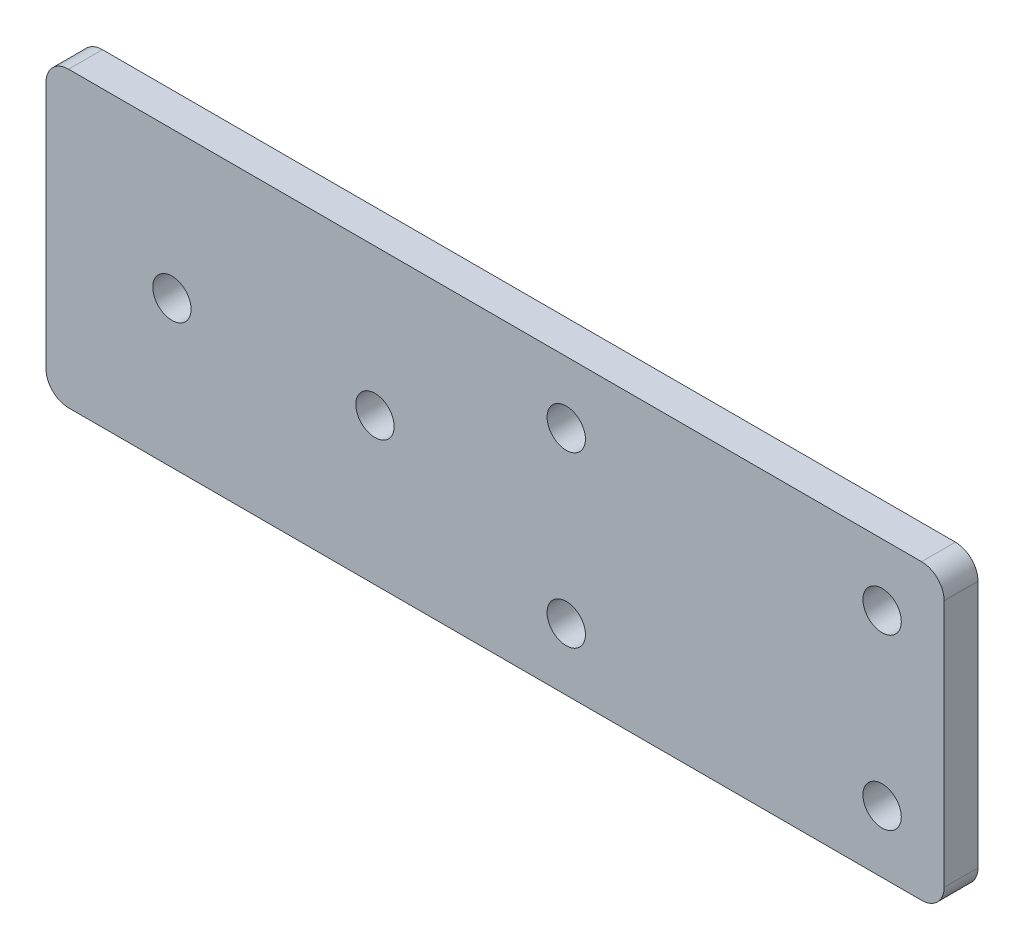
SolidWorks part; units mm, degrees
ref_plane "Plano frontal" through (0, 0, 0) normal (0, 0, 1) x (1, 0, 0)
ref_plane "Plano superior" through (0, 0, 0) normal (0, 1, 0) x (1, 0, 0)
ref_plane "Plano direito" through (0, 0, 0) normal (1, 0, 0) x (0, 0, -1)
sketch "Sketch1" plane through (0, 0, 0) normal (0, 0, 1) x (1, 0, 0)
  line L1 (297.8817, -13) -> (377.5, -13)
  line L2 (297.8817, -13) -> (297.8817, 13)
  line L3 (297.8817, 13) -> (377.5, 13)
  line L4 (377.5, -13) -> (377.5, 13)
extrude "Boss-Extrude1" add sketch "Sketch1" along normal blind 3
hole_wizard "M3 Clearance Hole1" positions "Sketch3" profile "Sketch2" hole size "M3" standard "ISO"
sketch "Sketch3" plane through (0, 0, 3) normal (0, 0, 1) x (1, 0, 0)
  point P2 (372, -7.5)
  point P5 (372, 7.5)
  point P8 (344, 7.5)
  point P11 (344, -7.5)
sketch "Sketch2" plane through (372, -7.5, 3) normal (1, 0, 0) x (0, -1, 0)
  line L0 (0, 0) -> (0, 6.0215)
  line L1 (0, 6.0215) -> (1.7, 5)
  line L2 (1.7, 5) -> (1.7, 0)
  line L5 (1.7, 0) -> (0, 0)
  line L10 (0, 6.0215) -> (-1.7, 5) construction
  line L11 (0, -6.35) -> (0, 107.95) construction
  dimension "Hole Dia." = 3.4
  dimension "Hole Depth" = 5
  dimension "Drill Angle" = 118
hole_wizard "M3 Clearance Hole2" positions "Sketch5" profile "Sketch4" hole size "M3" standard "ISO"
sketch "Sketch5" plane through (0, 0, 3) normal (0, 0, 1) x (1, 0, 0)
  point P4 (309.0461, 0)
  point P8 (327.0461, 0)
sketch "Sketch4" plane through (309.0461, 0, 3) normal (1, 0, 0) x (0, -1, 0)
  line L0 (0, 0) -> (0, 6.0215)
  line L1 (0, 6.0215) -> (1.7, 5)
  line L2 (1.7, 5) -> (1.7, 0)
  line L5 (1.7, 0) -> (0, 0)
  line L10 (0, 6.0215) -> (-1.7, 5) construction
  line L11 (0, -6.35) -> (0, 107.95) construction
  dimension "Hole Dia." = 3.4
  dimension "Hole Depth" = 5
  dimension "Drill Angle" = 118
fillet "Fillet1" radius 2 4 edges at (297.8817, -13, 1.5) (297.8817, 13, 1.5) (377.5, 13, 1.5) (377.5, -13, 1.5)
